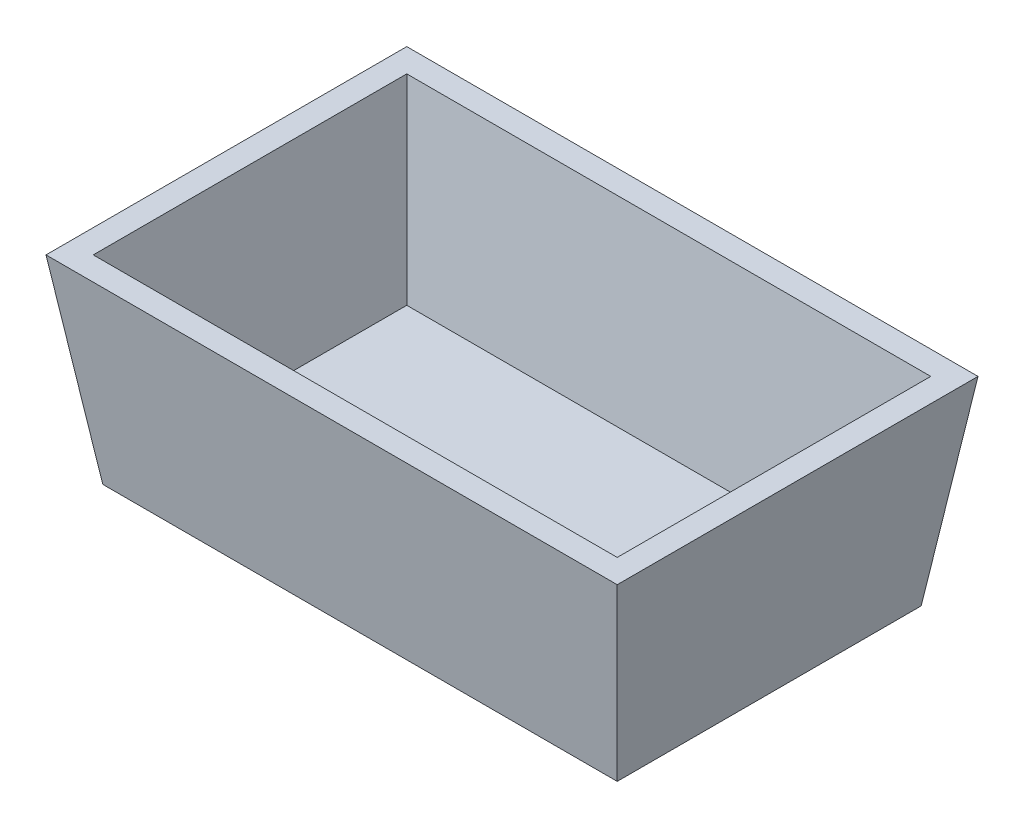
SolidWorks part; units mm, degrees
ref_plane "Front Plane" through (0, 0, 0) normal (0, 0, 1) x (1, 0, 0)
ref_plane "Top Plane" through (0, 0, 0) normal (0, 1, 0) x (1, 0, 0)
ref_plane "Right Plane" through (0, 0, 0) normal (1, 0, 0) x (0, 0, -1)
sketch "Sketch1" plane through (0, 0, 0) normal (0, 1, 0) x (1, 0, 0)
  line L1 (0, 0) -> (558.8, 0)
  line L2 (0, 0) -> (0, 330.2)
  line L3 (0, 330.2) -> (558.8, 330.2)
  line L4 (558.8, 0) -> (558.8, 330.2)
  dimension "D1" = 558.8
  dimension "D2" = 330.2
ref_plane "Plane1" through (0, 266.7, 0) normal (0, 1, 0) x (1, 0, 0)
sketch "Sketch2" plane through (0, 266.7, 0) normal (0, 1, 0) x (1, 0, 0)
  line L0 (0, 330.2) -> (558.8, 330.2) construction
  line L1 (-38.1, -38.1) -> (596.9, -38.1)
  line L2 (-38.1, -38.1) -> (-38.1, 368.3)
  line L3 (-38.1, 368.3) -> (596.9, 368.3)
  line L4 (596.9, -38.1) -> (596.9, 368.3)
  line L5 (0, 165.1) -> (558.8, 165.1) construction
  line L6 (0, 0) -> (0, 330.2) construction
  line L7 (558.8, 0) -> (558.8, 330.2) construction
  point P4 (279.4, 368.3)
  point P7 (279.4, 330.2)
  point P14 (-38.1, 165.1)
  dimension "D1" = 635
  dimension "D2" = 406.4
loft "Loft1" add profiles "Sketch2", "Sketch1"
shell "Shell1" thickness 25.4
ref_plane "Plane2" through (0, 215.9, 0) normal (0, 1, 0) x (1, 0, 0)
sketch "Sketch5" plane through (0, 215.9, 0) normal (0, 1, 0) x (1, 0, 0)
  line L1 (-191.5307, 447.8734) -> (738.1452, 447.8734)
  line L2 (-191.5307, 447.8734) -> (-191.5307, -111.2223)
  line L3 (-191.5307, -111.2223) -> (738.1452, -111.2223)
  line L4 (738.1452, 447.8734) -> (738.1452, -111.2223)
extrude "Cut-Extrude1" cut sketch "Sketch5" along normal up to surface (50.8 mm away) up to face at (279.4, 266.7, -165.1)
sketch "Sketch6" plane through (0, 215.9, 0) normal (0, 1, 0) x (1, 0, 0)
  line L0 (-18.0139, 335.385) -> (-18.0139, -5.185)
  line L1 (-5.185, 335.385) -> (-30.8429, 361.0429) construction
  line L2 (-5.185, -5.185) -> (-30.8429, -30.8429) construction
  line L4 (-5.185, 335.385) -> (-5.185, -5.185)
  line L6 (-5.185, 335.385) -> (-18.0139, 335.385)
  line L7 (-5.185, -5.185) -> (-18.0139, -5.185)
  line L8 (-18.0139, -18.0139) -> (-18.0139, 348.2139) construction
  line L9 (279.4, 361.0429) -> (279.4, -30.8429) construction
  line L10 (-30.8429, 361.0429) -> (589.6429, 361.0429) construction
  line L11 (589.6429, -30.8429) -> (-30.8429, -30.8429) construction
  line L12 (563.985, 335.385) -> (576.8139, 335.385)
  line L13 (563.985, 335.385) -> (563.985, -5.185)
  line L14 (563.985, -5.185) -> (576.8139, -5.185)
  line L15 (576.8139, 335.385) -> (576.8139, -5.185)
  point P10 (-18.0139, -18.0139)
  point P11 (-18.0139, 348.2139)
